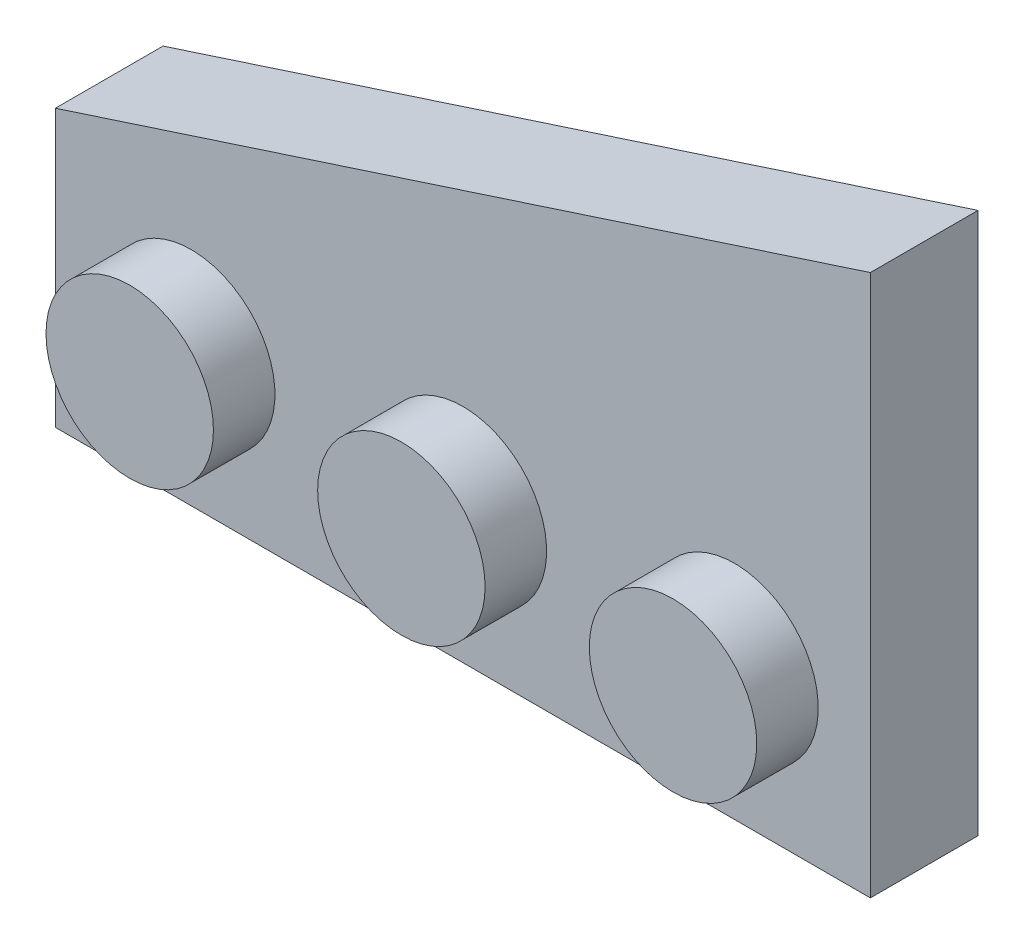
SolidWorks part; units mm, degrees
ref_plane "Front Plane" through (0, 0, 0) normal (0, 0, 1) x (1, 0, 0)
ref_plane "Top Plane" through (0, 0, 0) normal (0, 1, 0) x (1, 0, 0)
ref_plane "Right Plane" through (0, 0, 0) normal (1, 0, 0) x (0, 0, -1)
sketch "Sketch1" plane through (0, 0, 0) normal (0, 0, 1) x (1, 0, 0)
  line L0 (0, 15.85) -> (0, 0)
  line L1 (0, 0) -> (-23.85, 0)
  line L2 (-23.85, 0) -> (-23.85, 8.09)
  line L3 (-23.85, 8.09) -> (0, 15.85)
  point P4 (0, 0)
  dimension "D1" = 23.85
  dimension "D2" = 15.85
  dimension "D3" = 8.09
extrude "Boss-Extrude1" add sketch "Sketch1" against normal blind 3.15
sketch "Sketch2" plane through (0, 0, 0) normal (0, 0, 1) x (1, 0, 0)
  line L0 (0, 0) -> (0, 15.85) construction
  line L1 (-23.85, 0) -> (0, 0) construction
  circle A0 centre (-3.975, 4.045) radius 2.45
  circle A1 centre (-11.925, 4.045) radius 2.45
  circle A2 centre (-19.875, 4.045) radius 2.45
  dimension "D1" = 3.975
  dimension "D3" = 4.9
  dimension "D5" = 7.95
  dimension "D2" = 4.045
  dimension "D4" = 3
extrude "Boss-Extrude2" add sketch "Sketch2" along normal blind 1.8
shell "Shell1" thickness 1.5
